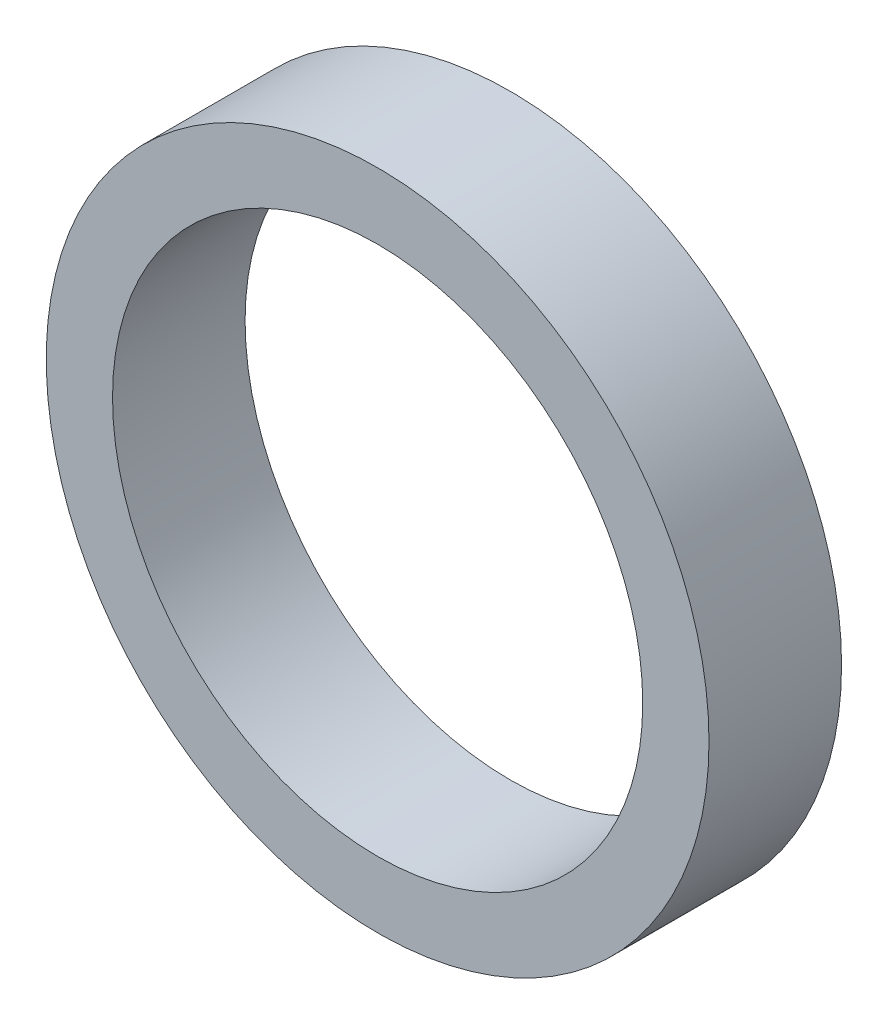
SolidWorks part; units mm, degrees
ref_plane "Front Plane" through (0, 0, 0) normal (0, 0, 1) x (1, 0, 0)
ref_plane "Top Plane" through (0, 0, 0) normal (0, 1, 0) x (1, 0, 0)
ref_plane "Right Plane" through (0, 0, 0) normal (1, 0, 0) x (0, 0, -1)
sketch "Sketch1" plane through (0, 0, 0) normal (0, 0, 1) x (1, 0, 0)
  circle A0 centre (0, 0) radius 31.75
  dimension "D1" = 63.5
extrude "Boss-Extrude1" add sketch "Sketch1" along normal blind 12.7
sketch "Sketch2" plane through (0, 0, 12.7) normal (0, 0, 1) x (1, 0, 0)
  circle A0 centre (0, 0) radius 25.4
  dimension "D1" = 50.8
extrude "Cut-Extrude1" cut sketch "Sketch2" against normal through all
